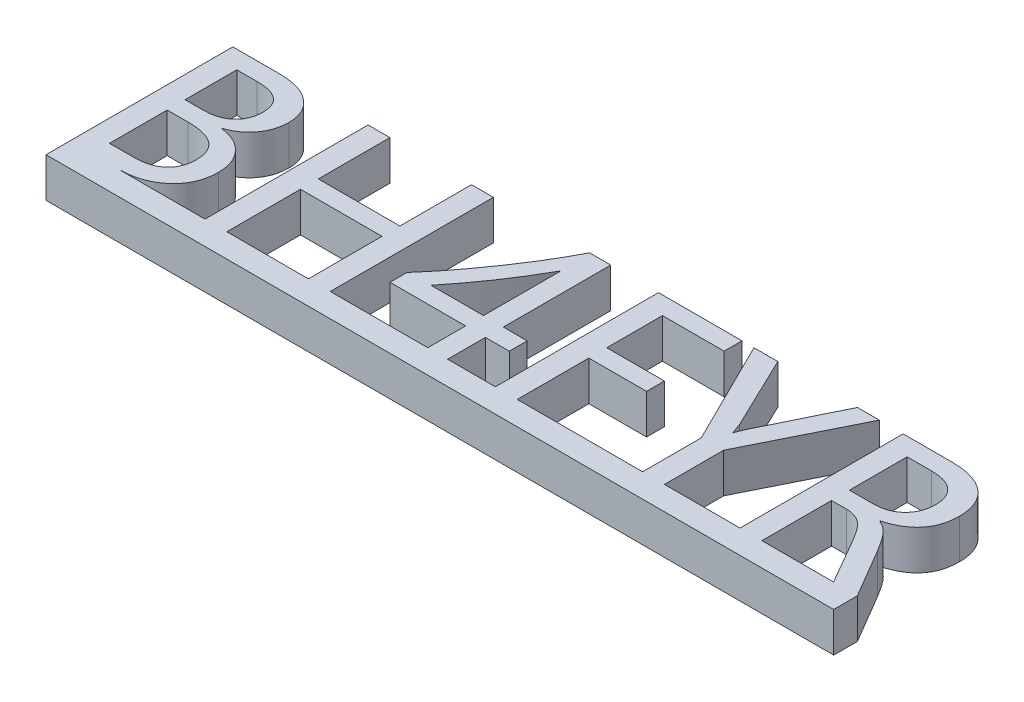
SolidWorks part; units mm, degrees
ref_plane "前视基准面" through (0, 0, 0) normal (0, 0, 1) x (1, 0, 0)
ref_plane "上视基准面" through (0, 0, 0) normal (0, 1, 0) x (1, 0, 0)
ref_plane "右视基准面" through (0, 0, 0) normal (1, 0, 0) x (0, 0, -1)
sketch "草图1" plane through (0, 0, 0) normal (0, 1, 0) x (1, 0, 0)
  text T0 "BH4FYR" font "微软雅黑" height in points 72
  point P1 (0, 0)
  point P2 (0, 0)
extrude "凸台-拉伸1" add sketch "草图1" along normal blind 5
sketch "草图2" plane through (0, 0, -13.5793) normal (0, 0, 1) x (1, 0, 0)
  line L1 (-60.6033, 5) -> (39.0009, 5)
  line L2 (-60.6033, 5) -> (-60.6033, 0)
  line L3 (-60.6033, 0) -> (39.0009, 0)
  line L4 (39.0009, 5) -> (39.0009, 0)
extrude "凸台-拉伸2" add sketch "草图2" along normal blind 3
